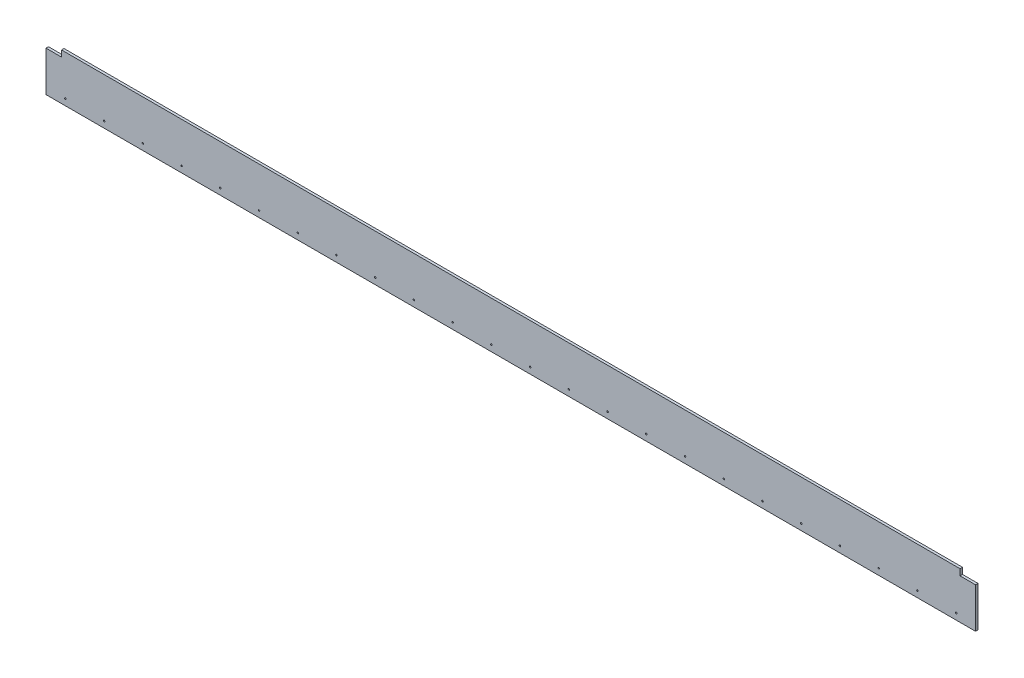
SolidWorks part; units mm, degrees
ref_plane "Plan de face" through (0, 0, 0) normal (0, 0, 1) x (1, 0, 0)
ref_plane "Plan de dessus" through (0, 0, 0) normal (0, 1, 0) x (1, 0, 0)
ref_plane "Plan de droite" through (0, 0, 0) normal (1, 0, 0) x (0, 0, -1)
sketch "Esquisse1" plane through (0, 0, 0) normal (0, 0, 1) x (1, 0, 0)
  line L1 (0, 0) -> (600, 0)
  line L2 (0, 0) -> (0, 30)
  line L3 (0, 30) -> (600, 30)
  line L4 (600, 0) -> (600, 30)
  dimension "D1" = 600
  dimension "D2" = 30
extrude "Boss.-Extru.1" add sketch "Esquisse1" along normal blind 1.6
sketch "Esquisse5" plane through (0, 0, 0) normal (0, 0, -1) x (-1, 0, 0)
  line L0 (-600, 0) -> (-600, 30) construction
  line L1 (0, 0) -> (-600, 0) construction
  circle A0 centre (-587.5, 4) radius 0.5
  dimension "D1" = 12.5
  dimension "D2" = 4
extrude "Enlèv. mat.-Extru.2" cut sketch "Esquisse5" against normal blind 50
pattern_linear "Répétition linéaire3" count 24 spacing 25 along (-1, 0, 0) of "Enlèv. mat.-Extru.2"
sketch "Esquisse6" plane through (0, 0, 0) normal (0, 0, -1) x (-1, 0, 0)
  line L1 (-600, 30) -> (-590, 30)
  line L2 (-600, 30) -> (-600, 26)
  line L3 (-600, 26) -> (-590, 26)
  line L4 (-590, 30) -> (-590, 26)
  line L5 (0, 30) -> (-10, 30)
  line L6 (0, 30) -> (0, 26)
  line L7 (0, 26) -> (-10, 26)
  line L8 (-10, 30) -> (-10, 26)
  dimension "D1" = 4
  dimension "D2" = 10
  dimension "D3" = 4
  dimension "D4" = 10
extrude "Enlèv. mat.-Extru.3" cut sketch "Esquisse6" against normal blind 30
